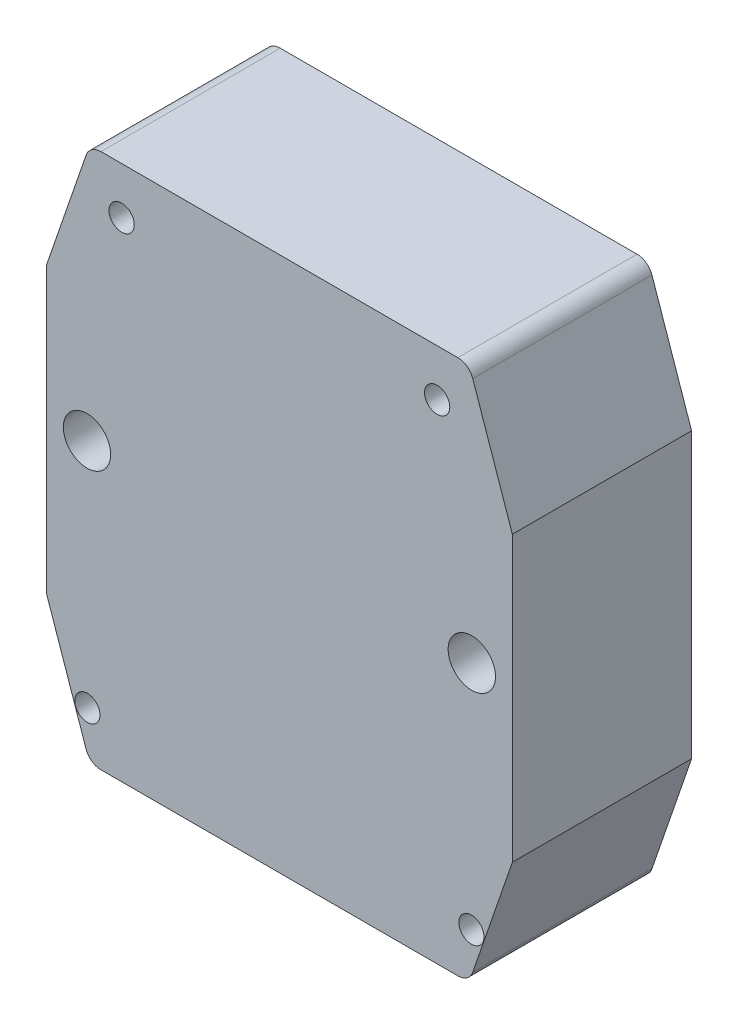
SolidWorks part; units mm, degrees
ref_plane "Front Plane" through (0, 0, 0) normal (0, 0, 1) x (1, 0, 0)
ref_plane "Top Plane" through (0, 0, 0) normal (0, 1, 0) x (1, 0, 0)
ref_plane "Right Plane" through (0, 0, 0) normal (1, 0, 0) x (0, 0, -1)
sketch "Sketch1" plane through (0, 0, 0) normal (0, 0, 1) x (1, 0, 0)
  line L0 (65.396, 51.9233) -> (57.425, 75.0726) construction
  line L1 (54.423, 77.214) -> (-17.4064, 77.214) construction
  line L2 (-20.4084, 75.0726) -> (-28.3794, 51.9233) construction
  line L3 (65.396, 51.9233) -> (57.425, 75.0726)
  line L4 (54.423, 77.214) -> (-17.4064, 77.214)
  line L5 (-20.4084, 75.0726) -> (-28.3794, 51.9233)
  line L6 (65.396, -5.2447) -> (57.425, -28.3941)
  line L7 (-20.4084, -28.3941) -> (-28.3794, -5.2447)
  line L8 (54.423, -30.5354) -> (-17.4064, -30.5354)
  line L9 (-13.2417, 67.7855) -> (57.1544, -21.1069) construction
  line L10 (21.9564, 23.3393) -> (43.3343, 23.3393) construction
  line L11 (-28.3794, 51.9233) -> (-28.3794, -5.2447)
  line L12 (65.396, 51.9233) -> (65.396, -5.2447)
  arc A0 (57.425, 75.0726) -> (54.423, 77.214) centre (54.423, 74.039) ccw construction
  arc A1 (-17.4064, 77.214) -> (-20.4084, 75.0726) centre (-17.4064, 74.039) ccw construction
  arc A2 (57.425, 75.0726) -> (54.423, 77.214) centre (54.423, 74.039) ccw
  arc A3 (-17.4064, 77.214) -> (-20.4084, 75.0726) centre (-17.4064, 74.039) ccw
  circle A4 centre (-13.2417, 67.7855) radius 2.54 construction
  circle A5 centre (-13.2417, 67.7855) radius 2.54
  circle A6 centre (50.2583, 67.7855) radius 2.54 construction
  circle A7 centre (50.2583, 67.7855) radius 2.54
  circle A8 centre (-20.1378, -21.1069) radius 2.54 construction
  circle A9 centre (-20.1378, -21.1069) radius 2.54
  circle A10 centre (57.1544, -21.1069) radius 2.54 construction
  circle A11 centre (57.1544, -21.1069) radius 2.54
  circle A12 centre (-20.216, 25.398) radius 4.7625 construction
  circle A13 centre (-20.216, 25.398) radius 4.7625
  circle A14 centre (57.2326, 25.398) radius 4.7625 construction
  circle A15 centre (57.2326, 25.398) radius 4.7625
  arc A16 (57.425, -28.3941) -> (54.423, -30.5354) centre (54.423, -27.3604) cw
  arc A17 (-17.4064, -30.5354) -> (-20.4084, -28.3941) centre (-17.4064, -27.3604) cw
extrude "Boss-Extrude1" add sketch "Sketch1" along normal blind 36.068
